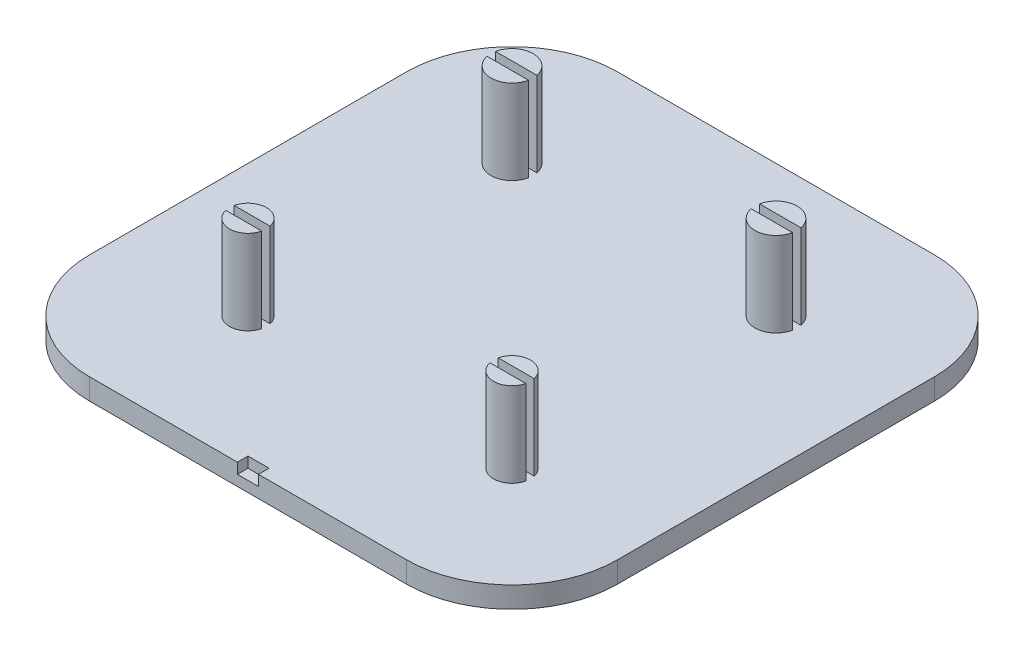
SolidWorks part; units mm, degrees
ref_plane "Front Plane" through (0, 0, 0) normal (0, 0, 1) x (1, 0, 0)
ref_plane "Top Plane" through (0, 0, 0) normal (0, 1, 0) x (1, 0, 0)
ref_plane "Right Plane" through (0, 0, 0) normal (1, 0, 0) x (0, 0, -1)
sketch "Sketch1" plane through (0, 0, 0) normal (0, 1, 0) x (1, 0, 0)
  line L1 (-203.8869, 1.4627) -> (-153.8869, 1.4627)
  line L2 (-203.8869, 1.4627) -> (-203.8869, -48.5373)
  line L3 (-203.8869, -48.5373) -> (-153.8869, -48.5373)
  line L4 (-153.8869, 1.4627) -> (-153.8869, -48.5373)
extrude "Boss-Extrude1" add sketch "Sketch1" along normal blind 2
sketch "Sketch2" plane through (0, 2, 0) normal (0, 1, 0) x (1, 0, 0)
  line L0 (-178.8869, -23.5373) -> (-178.8869, 1.4627)
  line L1 (-166.3869, -11.0373) -> (-166.3869, -10.6373)
  line L2 (-166.3869, -10.6373) -> (-169.2134, -10.6373)
  line L3 (-178.8869, -23.5373) -> (-153.8869, -23.5373)
  line L4 (-191.3869, -36.0373) -> (-191.3869, -35.6373)
  line L5 (-169.2134, -10.6373) -> (-163.6137, -10.6373)
  line L6 (-153.8869, 1.4627) -> (-203.8869, 1.4627) construction
  line L7 (-178.8869, -23.5373) -> (-178.8869, -48.5373)
  line L8 (-203.8869, -48.5373) -> (-153.8869, -48.5373) construction
  line L9 (-153.8869, -48.5373) -> (-153.8869, 1.4627) construction
  line L10 (-178.8869, -23.5373) -> (-203.8869, -23.5373)
  line L11 (-203.8869, 1.4627) -> (-203.8869, -48.5373) construction
  line L12 (-191.3869, -11.0373) -> (-191.3869, -10.6373)
  line L13 (-191.3869, -10.6373) -> (-194.3433, -10.6373)
  line L14 (-169.2134, -10.6373) -> (-169.2134, -11.4373)
  line L15 (-194.3433, -10.6373) -> (-188.6112, -10.6373)
  line L16 (-194.3433, -10.6373) -> (-194.3433, -11.4373)
  line L17 (-194.3433, -11.4373) -> (-188.6112, -11.4373)
  line L18 (-188.6112, -10.6373) -> (-188.6112, -11.4373)
  line L19 (-169.2134, -11.4373) -> (-163.6137, -11.4373)
  line L20 (-163.6137, -10.6373) -> (-163.6137, -11.4373)
  line L21 (-191.3869, -35.6373) -> (-194.1386, -35.6373)
  line L22 (-166.3869, -36.0373) -> (-166.3869, -35.6373)
  line L23 (-194.1386, -35.6373) -> (-188.6112, -35.6373)
  line L24 (-194.1386, -35.6373) -> (-194.1386, -36.4373)
  line L25 (-194.1386, -36.4373) -> (-188.6112, -36.4373)
  line L26 (-188.6112, -35.6373) -> (-188.6112, -36.4373)
  line L27 (-166.3869, -35.6373) -> (-169.0191, -35.6373)
  line L29 (-169.0191, -35.6373) -> (-162.9133, -35.6373)
  line L30 (-169.0191, -35.6373) -> (-169.0191, -36.4373)
  line L31 (-169.0191, -36.4373) -> (-162.9133, -36.4373)
  line L32 (-162.9133, -35.6373) -> (-162.9133, -36.4373)
  circle A0 centre (-191.3869, -11.0373) radius 2
  circle A1 centre (-166.3869, -11.0373) radius 2
  circle A2 centre (-191.3869, -36.0373) radius 1.75
  circle A3 centre (-166.3869, -36.0373) radius 1.75
  point P41 (0, 0)
extrude "Boss-Extrude2" add sketch "Sketch2" along normal blind 8 contours L25 A2 | L23 A2 L21 | L29 A3 L27 | L31 A3 | L15 A0 L13 | L17 A0 | L5 A1 L2 | L19 A1
fillet "Fillet1" radius 10 4 edges at (-153.8869, 1, -1.4627) (-153.8869, 1, 48.5373) (-203.8869, 1, 48.5373) (-203.8869, 1, -1.4627)
sketch "Sketch3" plane through (0, 2, 0) normal (0, 1, 0) x (1, 0, 0)
  line L0 (-178.8869, 1.4627) -> (-179.8869, 1.4627)
  line L1 (-193.8869, -48.5373) -> (-163.8869, -48.5373) construction
  line L2 (-178.8869, -47.5373) -> (-179.8869, -47.5373)
  line L3 (-179.8869, -47.5373) -> (-179.8869, -48.5373)
  line L4 (-178.8869, -47.5373) -> (-177.8869, -47.5373)
  line L5 (-177.8869, -47.5373) -> (-177.8869, -48.5373)
  line L6 (-177.8869, -48.5373) -> (-179.8869, -48.5373)
  line L7 (-163.8869, 1.4627) -> (-193.8869, 1.4627) construction
  line M24 (-193.8869, -48.5373) -> (-163.8869, -48.5373)
extrude "Cut-Extrude1" cut sketch "Sketch3" against normal blind 1 contours L5 L4 L2 L3 M24
